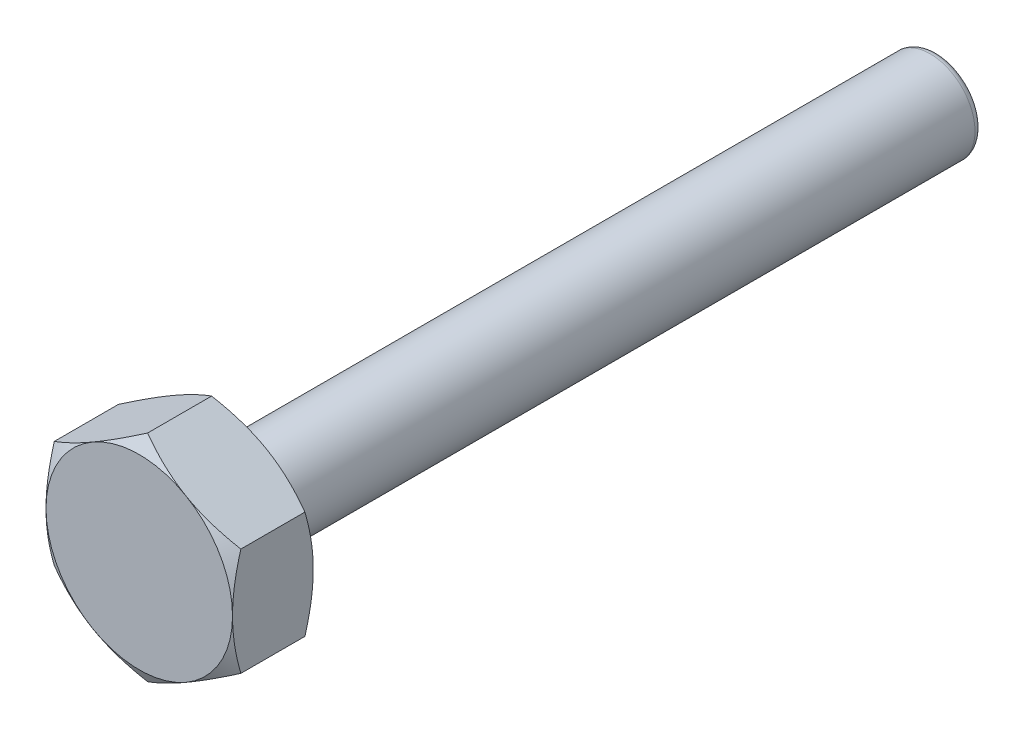
SolidWorks part; units mm, degrees
ref_plane "Front Plane" through (0, 0, 0) normal (0, 0, 1) x (1, 0, 0)
ref_plane "Top Plane" through (0, 0, 0) normal (0, 1, 0) x (1, 0, 0)
ref_plane "Right Plane" through (0, 0, 0) normal (1, 0, 0) x (0, 0, -1)
sketch "Sketch1" plane through (0, 0, 0) normal (0, 0, 1) x (1, 0, 0)
  line L1 (52, 30.0222) -> (0, 60.0444)
  line L2 (0, 60.0444) -> (-52, 30.0222)
  line L3 (-52, 30.0222) -> (-52, -30.0222)
  line L4 (-52, -30.0222) -> (0, -60.0444)
  line L5 (0, -60.0444) -> (52, -30.0222)
  line L6 (52, -30.0222) -> (52, 30.0222)
  circle A0 centre (0, 0) radius 52 construction
  dimension "D1" = 104
  dimension "D2" = 104
extrude "Boss-Extrude1" add sketch "Sketch1" along normal mid plane 45
sketch "Sketch2" plane through (0, 0, 22.5) normal (0, 0, 1) x (1, 0, 0)
  circle A0 centre (0, 0) radius 52
extrude "Cut-Extrude1" cut sketch "Sketch2" against normal blind 45 draft 60 flip side to cut
sketch "Sketch3" plane through (0, 0, -22.5) normal (0, 0, -1) x (-1, 0, 0)
  circle A0 centre (0, 0) radius 52
extrude "Cut-Extrude2" cut sketch "Sketch3" against normal blind 45 draft 60 flip side to cut
sketch "Sketch4" plane through (0, 0, -22.5) normal (0, 0, -1) x (-1, 0, 0)
  circle A0 centre (0, 0) radius 25
  dimension "D1" = 50
extrude "Boss-Extrude2" add sketch "Sketch4" along normal blind 400
fillet "Fillet1" radius 4 1 edges at (-25, 0, -422.5)
